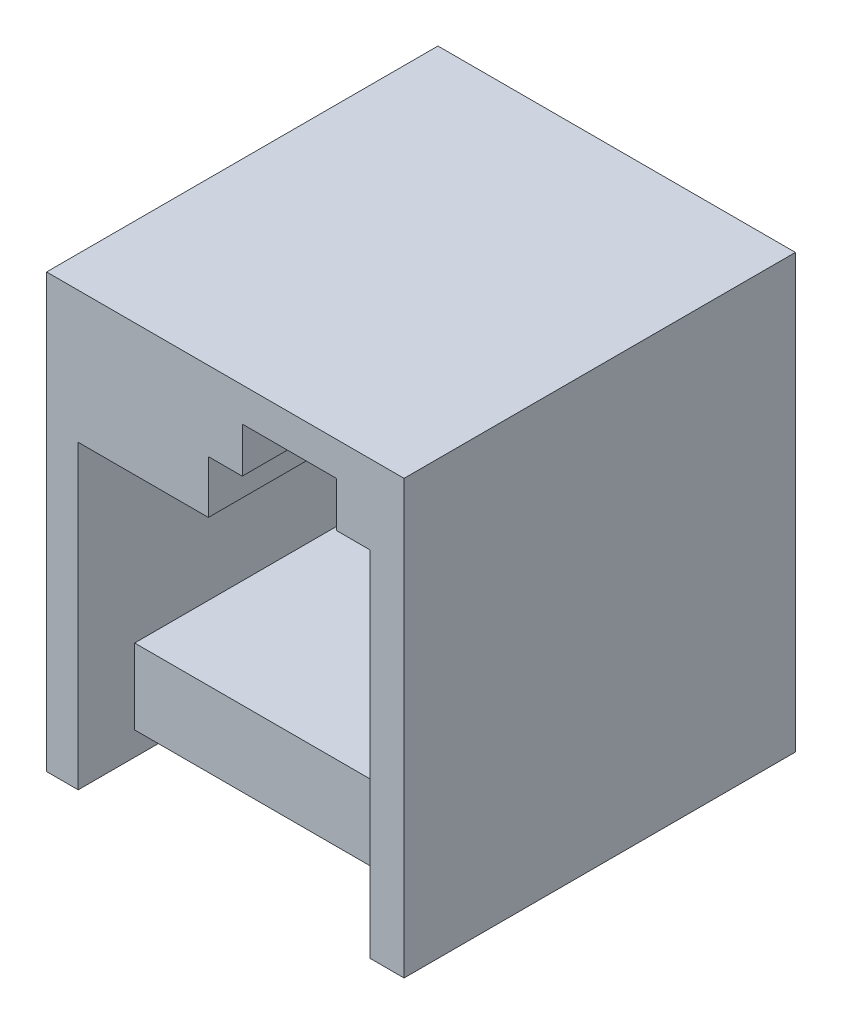
SolidWorks part; units mm, degrees
ref_plane "Front Plane" through (0, 0, 0) normal (0, 0, 1) x (1, 0, 0)
ref_plane "Top Plane" through (0, 0, 0) normal (0, 1, 0) x (1, 0, 0)
ref_plane "Right Plane" through (0, 0, 0) normal (1, 0, 0) x (0, 0, -1)
sketch "Sketch1" plane through (0, 0, 0) normal (0, 0, 1) x (1, 0, 0)
  line L0 (0, 0) -> (0, 14.605)
  line L1 (0, 14.605) -> (12.065, 14.605)
  line L2 (12.065, 14.605) -> (12.065, 0)
  line L3 (12.065, 0) -> (10.922, 0)
  line L4 (1.0668, 0) -> (1.0668, 10.16)
  line L5 (1.0668, 10.16) -> (5.461, 10.16)
  line L6 (5.461, 10.16) -> (5.461, 11.938)
  line L7 (5.461, 11.938) -> (6.604, 11.938)
  line L8 (6.604, 11.938) -> (6.604, 13.462)
  line L9 (6.604, 13.462) -> (9.779, 13.462)
  line L10 (9.779, 13.462) -> (9.779, 11.938)
  line L11 (9.779, 11.938) -> (10.922, 11.938)
  line L12 (10.922, 11.938) -> (10.922, 0)
  line L13 (1.0668, 0) -> (0, 0)
  dimension "D1" = 12.065
  dimension "D2" = 14.605
  dimension "D3" = 1.0668
  dimension "D4" = 4.445
  dimension "D5" = 1.778
  dimension "D6" = 1.143
  dimension "D7" = 2.667
  dimension "D8" = 1.143
  dimension "D9" = 5.461
  dimension "D10" = 2.286
  dimension "D11" = 3.175
extrude "Extrude1" add sketch "Sketch1" along normal blind 2.032
sketch "Sketch2" plane through (0, 0, 2.032) normal (0, 0, 1) x (1, 0, 0)
  line L0 (1.0668, 0.8001) -> (10.922, 0.8001)
  line L2 (10.922, 3.3401) -> (1.0668, 3.3401)
  line L4 (1.0668, 3.3401) -> (1.0668, 9.5367)
  line L5 (10.922, 0.8001) -> (10.922, 13.3817)
  line L14 (0, 0) -> (1.0668, 0)
  line L15 (1.0668, 0) -> (1.0668, 10.16)
  line L16 (1.0668, 10.16) -> (5.461, 10.16)
  line L17 (5.461, 10.16) -> (5.461, 11.938)
  line L18 (5.461, 11.938) -> (6.604, 11.938)
  line L19 (6.604, 11.938) -> (6.604, 13.462)
  line L20 (6.604, 13.462) -> (9.779, 13.462)
  line L21 (9.779, 13.462) -> (9.779, 11.938)
  line L22 (9.779, 11.938) -> (10.922, 11.938)
  line L23 (10.922, 11.938) -> (10.922, 0)
  line L24 (10.922, 0) -> (12.065, 0)
  line L25 (12.065, 0) -> (12.065, 14.605)
  line L26 (12.065, 14.605) -> (0, 14.605)
  line L27 (0, 14.605) -> (0, 0)
  line L28 (0, 0) -> (1.0668, 0)
  line L29 (1.0668, 0) -> (1.0668, 0.8001)
  line L30 (1.0668, 10.16) -> (5.461, 10.16)
  line L31 (5.461, 10.16) -> (5.461, 11.938)
  line L32 (5.461, 11.938) -> (6.604, 11.938)
  line L33 (6.604, 11.938) -> (6.604, 13.462)
  line L34 (6.604, 13.462) -> (9.779, 13.462)
  line L35 (9.779, 13.462) -> (9.779, 11.938)
  line L36 (9.779, 11.938) -> (10.922, 11.938)
  line L37 (10.922, 11.938) -> (10.922, 3.3401)
  line L38 (10.922, 0) -> (12.065, 0)
  line L40 (12.065, 14.605) -> (0, 14.605)
  line L41 (0, 14.605) -> (0, 0)
  line M15 (0, 0) -> (1.0668, 0)
  line M16 (1.0668, 0) -> (1.0668, 10.16)
  line M17 (1.0668, 10.16) -> (5.461, 10.16)
  line M18 (5.461, 10.16) -> (5.461, 11.938)
  line M19 (5.461, 11.938) -> (6.604, 11.938)
  line M20 (6.604, 11.938) -> (6.604, 13.462)
  line M21 (6.604, 13.462) -> (9.779, 13.462)
  line M22 (9.779, 13.462) -> (9.779, 11.938)
  line M23 (9.779, 11.938) -> (10.922, 11.938)
  line M24 (10.922, 11.938) -> (10.922, 0)
  line M25 (10.922, 0) -> (12.065, 0)
  line M26 (12.065, 0) -> (12.065, 14.605)
  line M27 (12.065, 14.605) -> (0, 14.605)
  line M28 (0, 14.605) -> (0, 0)
  dimension "D2" = 2.54
  dimension "D3" = 3.3401
  dimension "D1" = 0
extrude "Extrude3" add sketch "Sketch2" against normal blind 11.303 contours M28 M15 M16 M17 M18 M19 M20 M21 M22 M23 M24 M25 M26 M27 | L2 L0 M24 M16
sketch "Sketch3" plane through (0, 0, 2.032) normal (0, 0, 1) x (1, 0, 0)
  line L1 (1.0668, 0.8001) -> (10.922, 0.8001)
  line L2 (1.0668, 0.8001) -> (1.0668, 3.3401)
  line L3 (1.0668, 3.3401) -> (10.922, 3.3401)
  line L4 (10.922, 0.8001) -> (10.922, 3.3401)
extrude "Extrude4" cut sketch "Sketch3" against normal blind 1.905
sketch "Sketch4" plane through (0, 0, -9.271) normal (0, 0, -1) x (-1, 0, 0)
  line L1 (-12.065, 14.605) -> (0, 14.605)
  line L2 (-12.065, 14.605) -> (-12.065, 0)
  line L3 (-12.065, 0) -> (0, 0)
  line L4 (0, 14.605) -> (0, 0)
extrude "Extrude5" add sketch "Sketch4" along normal blind 1.905
